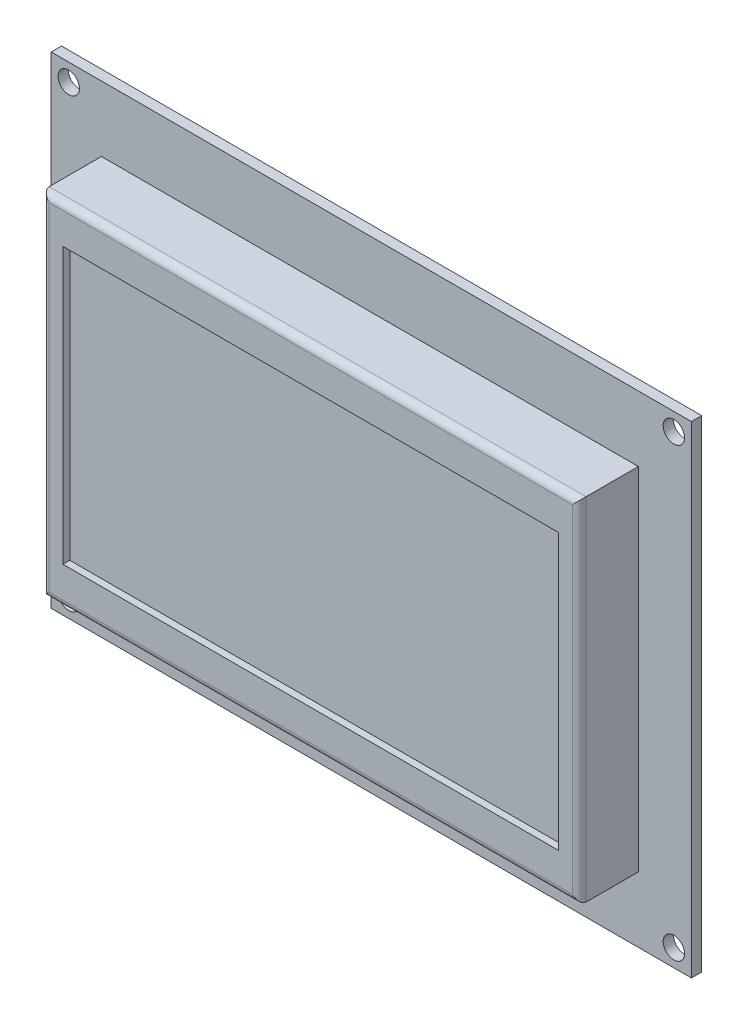
SolidWorks part; units mm, degrees
ref_plane "Alzado" through (0, 0, 0) normal (0, 0, 1) x (1, 0, 0)
ref_plane "Planta" through (0, 0, 0) normal (0, 1, 0) x (1, 0, 0)
ref_plane "Vista lateral" through (0, 0, 0) normal (1, 0, 0) x (0, 0, -1)
ref_plane "Plano1" through (0, 0, 6) normal (0, 0, 1) x (1, 0, 0)
sketch "Croquis1" plane through (0, 0, 6) normal (0, 0, 1) x (1, 0, 0)
  line L0 (46.5, -26.5) -> (46.5, 43.5)
  line L1 (46.5, 43.5) -> (-46.5, 43.5)
  line L2 (-46.5, 43.5) -> (-46.5, -26.5)
  line L3 (-46.5, -26.5) -> (46.5, -26.5)
extrude "Saliente-Extruir1" add sketch "Croquis1" against normal blind 1.5
sketch "Croquis2" plane through (0, 0, 6) normal (0, 0, 1) x (1, 0, 0)
  line L0 (-39.2, -17) -> (-39.2, 34)
  line L1 (-39.2, 34) -> (38.8, 34)
  line L2 (38.8, 34) -> (38.8, -17)
  line L3 (38.8, -17) -> (-39.2, -17)
extrude "Saliente-Extruir2" add sketch "Croquis2" along normal blind 8.6
hole_wizard "Diámetro de taladro Ø3.1 (3.1)1" positions "Croquis4" profile "Croquis3" hole size "Ø3.1" standard "Ansi Metric"
sketch "Croquis4" plane through (0, 0, 4.5) normal (0, 0, -1) x (-1, 0, 0)
  point P0 (43.95, -23.95)
  point P1 (-43.95, -23.95)
  point P2 (43.95, 40.95)
  point P3 (-43.95, 40.95)
sketch "Croquis3" plane through (-43.95, -23.95, 4.5) normal (1, 0, 0) x (0, 1, 0)
  line L0 (0, 0) -> (0, 10.1)
  line L1 (0, 10.1) -> (1.55, 10.1)
  line L2 (1.55, 10.1) -> (1.55, 0)
  line L5 (1.55, 0) -> (0, 0)
  line L11 (0, -6.35) -> (0, 107.95) construction
  dimension "Diámetro de taladro hasta el siguiente" = 3.1
  dimension "Profundidad de taladro hasta el siguiente" = 10.1
fillet "Redondeo1" radius 1 4 edges at (-0.2, 34, 14.6) (38.8, 8.5, 14.6) (-39.2, 8.5, 14.6) (-0.2, -17, 14.6)
sketch "Croquis5" plane through (0, 0, 14.6) normal (0, 0, 1) x (1, 0, 0)
  line L0 (-0.2, 33) -> (-0.2, -16) construction
  line L1 (-36.2, -11.5) -> (35.8, -11.5)
  line L2 (-36.2, -11.5) -> (-36.2, 28.5)
  line L3 (-36.2, 28.5) -> (35.8, 28.5)
  line L4 (35.8, -11.5) -> (35.8, 28.5)
  line L5 (-36.2, -11.5) -> (35.8, 28.5) construction
  line L6 (-36.2, 28.5) -> (35.8, -11.5) construction
extrude "Cortar-Extruir1" cut sketch "Croquis5" against normal blind 1
